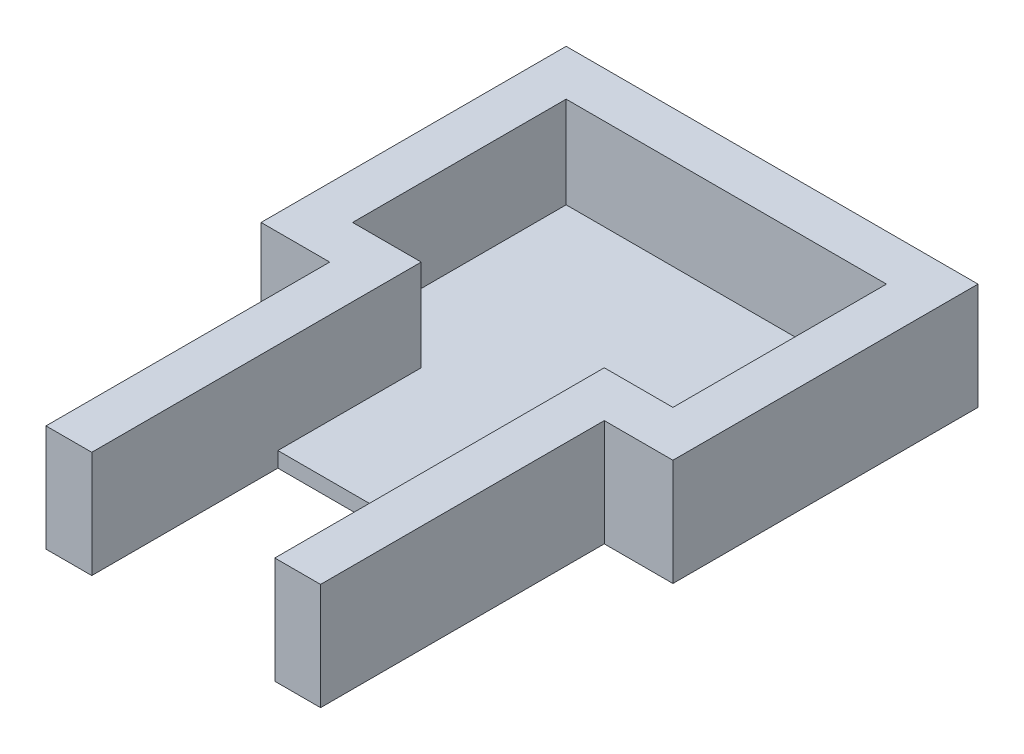
SolidWorks part; units mm, degrees
ref_plane "Front Plane" through (0, 0, 0) normal (0, 0, 1) x (1, 0, 0)
ref_plane "Top Plane" through (0, 0, 0) normal (0, 1, 0) x (1, 0, 0)
ref_plane "Right Plane" through (0, 0, 0) normal (1, 0, 0) x (0, 0, -1)
sketch "Sketch1" plane through (0, 0, 0) normal (0, 1, 0) x (1, 0, 0)
  line L0 (0, 0) -> (0, -96.5) construction
  line L1 (67.5, -50) -> (45, -50)
  line L2 (67.5, -50) -> (67.5, 50)
  line L3 (67.5, 50) -> (-67.5, 50)
  line L4 (-67.5, -50) -> (-67.5, 50)
  line L5 (67.5, -50) -> (-67.5, 50) construction
  line L6 (67.5, 50) -> (-67.5, -50) construction
  line L7 (-45, -50) -> (-67.5, -50)
  line L8 (45, -143) -> (-45, -143)
  line L9 (45, -143) -> (45, -50)
  line L11 (-45, -143) -> (-45, -50)
  line L12 (45, -143) -> (-45, -50) construction
  line L13 (45, -50) -> (-45, -143) construction
  point P0 (0, 0)
  dimension "D1" = 135
  dimension "D2" = 100
  dimension "D3" = 93
  dimension "D4" = 90
extrude "Boss-Extrude1" add sketch "Sketch1" along normal blind 5
sketch "Sketch2" plane through (0, 5, 0) normal (0, 1, 0) x (1, 0, 0)
  line L0 (-67.5, 50) -> (-67.5, -50)
  line L1 (-67.5, -50) -> (-45, -50)
  line L2 (-45, -50) -> (-45, -143)
  line L3 (-45, -143) -> (45, -143)
  line L4 (45, -143) -> (45, -50)
  line L5 (45, -50) -> (67.5, -50)
  line L6 (67.5, -50) -> (67.5, 50)
  line L7 (67.5, 50) -> (-67.5, 50)
  line L8 (52.5, 35) -> (-52.5, 35)
  line L9 (-52.5, 35) -> (-52.5, -35)
  line L10 (-52.5, -35) -> (-30, -35)
  line L11 (-30, -35) -> (-30, -128)
  line L12 (-30, -128) -> (30, -128)
  line L13 (30, -128) -> (30, -35)
  line L14 (30, -35) -> (52.5, -35)
  line L15 (52.5, -35) -> (52.5, 35)
  dimension "D1" = 15
extrude "Boss-Extrude2" add sketch "Sketch2" along normal blind 30
sketch "Sketch3" plane through (0, 35, 0) normal (0, 1, 0) x (1, 0, 0)
  line L0 (-45, -143) -> (45, -143) construction
  line L1 (-30, -143) -> (30, -143)
  line L2 (-30, -143) -> (-30, -82)
  line L3 (-30, -82) -> (30, -82)
  line L4 (30, -143) -> (30, -82)
  line L5 (30, -128) -> (30, -35) construction
  line L6 (-30, -35) -> (-30, -128) construction
  dimension "D1" = 61
extrude "Cut-Extrude1" cut sketch "Sketch3" against normal through all contours L2 L1 L4 L3
